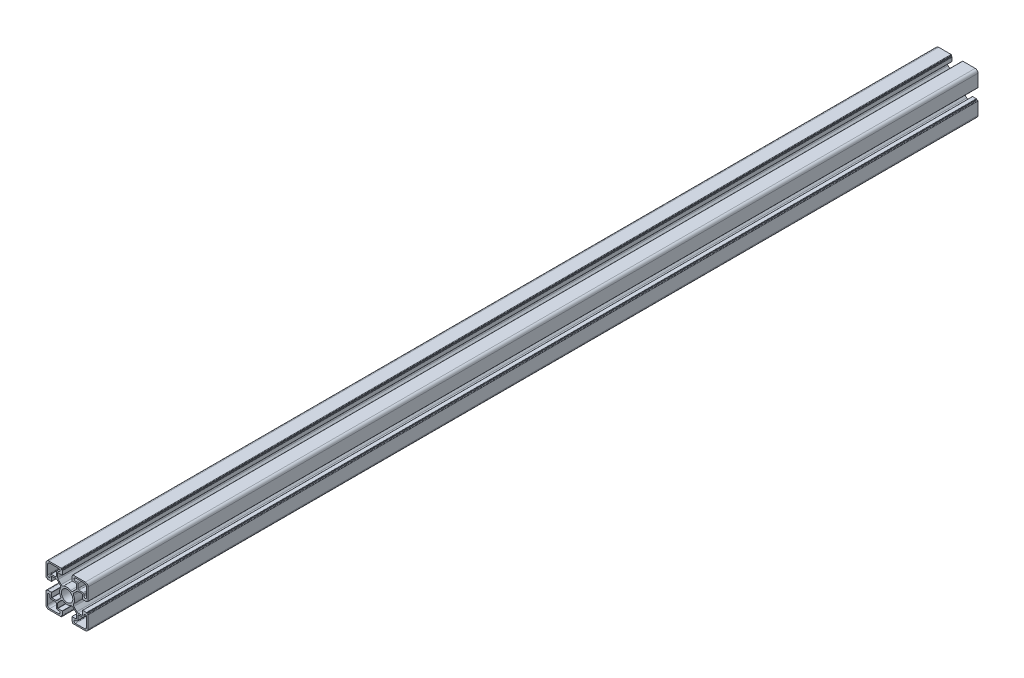
SolidWorks part; units mm, degrees
ref_plane "Front Plane" through (0, 0, 0) normal (0, 0, 1) x (1, 0, 0)
ref_plane "Top Plane" through (0, 0, 0) normal (0, 1, 0) x (1, 0, 0)
ref_plane "Right Plane" through (0, 0, 0) normal (1, 0, 0) x (0, 0, -1)
sketch "Sketch1" plane through (0, 0, 0) normal (0, 0, 1) x (1, 0, 0)
  line L3 (-22.5, 19.5) -> (-22.5, 6.3)
  line L4 (-20.7, 5) -> (-16.7, 5)
  line L5 (-16.5, 5.2) -> (-16.5, 9.8)
  line L6 (-16.3, 10) -> (-11.8642, 10)
  line L7 (-10.4924, 9.4318) -> (-7.2967, 6.236)
  line L8 (-21, 18.5) -> (-21, 9)
  line L9 (-16.5, 5) -> (-16.5, 10) construction
  line L10 (-18, 9) -> (-18, 10.5)
  line L11 (-17, 11.5) -> (-12.5, 11.5)
  line L12 (-22, 5.8) -> (-21.3, 5.8)
  line L13 (-21, 5.5) -> (-21, 5.3)
  line L14 (-21, 22.5) -> (-21, 6.5) construction
  line L15 (-18, 11.5) -> (-10.4393, 11.5) construction
  line L16 (-10.4393, 11.5) -> (-5.1016, 6.1623) construction
  line L17 (-18, 6.5) -> (-18, 11.5) construction
  line L18 (-22.5, 22.5) -> (-22.5, 5) construction
  line L19 (-22.5, 5) -> (-16.5, 5) construction
  line L20 (-21, 6.5) -> (-18, 6.5) construction
  line L21 (-16.5, 10) -> (-11.0607, 10) construction
  line L22 (-11.0607, 10) -> (-6.1623, 5.1016) construction
  line L23 (-5.5, 21) -> (-5.3, 21)
  line L24 (-5.8, 22) -> (-5.8, 21.3)
  line L25 (-11.5, 17) -> (-11.5, 12.5)
  line L26 (-9, 18) -> (-10.5, 18)
  line L27 (-18.5, 21) -> (-9, 21)
  line L28 (-9.4318, 10.4924) -> (-6.236, 7.2967)
  line L29 (-10, 16.3) -> (-10, 11.8642)
  line L30 (-5.2, 16.5) -> (-9.8, 16.5)
  line L31 (-5, 20.7) -> (-5, 16.7)
  line L32 (-19.5, 22.5) -> (-6.3, 22.5)
  line L33 (19.5, 22.5) -> (6.3, 22.5)
  line L34 (5, 20.7) -> (5, 16.7)
  line L35 (5.2, 16.5) -> (9.8, 16.5)
  line L36 (10, 16.3) -> (10, 11.8642)
  line L37 (9.4318, 10.4924) -> (6.236, 7.2967)
  line L38 (18.5, 21) -> (9, 21)
  line L39 (9, 18) -> (10.5, 18)
  line L40 (11.5, 17) -> (11.5, 12.5)
  line L41 (5.8, 22) -> (5.8, 21.3)
  line L42 (5.5, 21) -> (5.3, 21)
  line L43 (21, 5.5) -> (21, 5.3)
  line L44 (22, 5.8) -> (21.3, 5.8)
  line L45 (17, 11.5) -> (12.5, 11.5)
  line L46 (18, 9) -> (18, 10.5)
  line L47 (21, 18.5) -> (21, 9)
  line L48 (10.4924, 9.4318) -> (7.2967, 6.236)
  line L49 (16.3, 10) -> (11.8642, 10)
  line L50 (16.5, 5.2) -> (16.5, 9.8)
  line L51 (20.7, 5) -> (16.7, 5)
  line L52 (22.5, 19.5) -> (22.5, 6.3)
  line L53 (22.5, -19.5) -> (22.5, -6.3)
  line L54 (20.7, -5) -> (16.7, -5)
  line L55 (16.5, -5.2) -> (16.5, -9.8)
  line L56 (16.3, -10) -> (11.8642, -10)
  line L57 (10.4924, -9.4318) -> (7.2967, -6.236)
  line L58 (21, -18.5) -> (21, -9)
  line L59 (18, -9) -> (18, -10.5)
  line L60 (17, -11.5) -> (12.5, -11.5)
  line L61 (22, -5.8) -> (21.3, -5.8)
  line L62 (21, -5.5) -> (21, -5.3)
  line L63 (5.5, -21) -> (5.3, -21)
  line L64 (5.8, -22) -> (5.8, -21.3)
  line L65 (11.5, -17) -> (11.5, -12.5)
  line L66 (9, -18) -> (10.5, -18)
  line L67 (18.5, -21) -> (9, -21)
  line L68 (9.4318, -10.4924) -> (6.236, -7.2967)
  line L69 (10, -16.3) -> (10, -11.8642)
  line L70 (5.2, -16.5) -> (9.8, -16.5)
  line L71 (5, -20.7) -> (5, -16.7)
  line L72 (19.5, -22.5) -> (6.3, -22.5)
  line L73 (-19.5, -22.5) -> (-6.3, -22.5)
  line L74 (-5, -20.7) -> (-5, -16.7)
  line L75 (-5.2, -16.5) -> (-9.8, -16.5)
  line L76 (-10, -16.3) -> (-10, -11.8642)
  line L77 (-9.4318, -10.4924) -> (-6.236, -7.2967)
  line L78 (-18.5, -21) -> (-9, -21)
  line L79 (-9, -18) -> (-10.5, -18)
  line L80 (-11.5, -17) -> (-11.5, -12.5)
  line L81 (-5.8, -22) -> (-5.8, -21.3)
  line L82 (-5.5, -21) -> (-5.3, -21)
  line L83 (-21, -5.5) -> (-21, -5.3)
  line L84 (-22, -5.8) -> (-21.3, -5.8)
  line L85 (-17, -11.5) -> (-12.5, -11.5)
  line L86 (-18, -9) -> (-18, -10.5)
  line L87 (-21, -18.5) -> (-21, -9)
  line L88 (-10.4924, -9.4318) -> (-7.2967, -6.236)
  line L89 (-16.3, -10) -> (-11.8642, -10)
  line L90 (-16.5, -5.2) -> (-16.5, -9.8)
  line L91 (-20.7, -5) -> (-16.7, -5)
  line L92 (-22.5, -19.5) -> (-22.5, -6.3)
  arc A0 (0, 6.1) -> (-6.1, 0) centre (0, 0) ccw
  arc A1 (-6.9766, 3.9149) -> (-8, 0) centre (0, 0) ccw
  arc A2 (-21, 9) -> (-18, 9) centre (-19.5, 9) ccw
  arc A3 (-22, 5.8) -> (-22.5, 6.3) centre (-22, 6.3) cw
  arc A4 (-21, 5.3) -> (-20.7, 5) centre (-20.7, 5.3) ccw
  arc A5 (-21.3, 5.8) -> (-21, 5.5) centre (-21.3, 5.5) cw
  arc A6 (-16.7, 5) -> (-16.5, 5.2) centre (-16.7, 5.2) ccw
  arc A7 (-16.5, 9.8) -> (-16.3, 10) centre (-16.3, 9.8) cw
  arc A8 (-7.2967, 6.236) -> (-6.9766, 3.9149) centre (-8.6685, 4.8643) cw
  arc A9 (-11.8642, 10) -> (-10.4924, 9.4318) centre (-11.8642, 8.06) cw
  arc A10 (-18, 10.5) -> (-17, 11.5) centre (-17, 10.5) cw
  arc A11 (-10.5, 18) -> (-11.5, 17) centre (-10.5, 17) ccw
  arc A12 (-10, 11.8642) -> (-9.4318, 10.4924) centre (-8.06, 11.8642) ccw
  arc A13 (-6.236, 7.2967) -> (-3.9149, 6.9766) centre (-4.8643, 8.6685) ccw
  arc A14 (-9.8, 16.5) -> (-10, 16.3) centre (-9.8, 16.3) ccw
  arc A15 (-5, 16.7) -> (-5.2, 16.5) centre (-5.2, 16.7) cw
  arc A16 (-5.8, 21.3) -> (-5.5, 21) centre (-5.5, 21.3) ccw
  arc A17 (-5.3, 21) -> (-5, 20.7) centre (-5.3, 20.7) cw
  arc A18 (-5.8, 22) -> (-6.3, 22.5) centre (-6.3, 22) ccw
  arc A19 (-9, 21) -> (-9, 18) centre (-9, 19.5) cw
  arc A20 (-3.9149, 6.9766) -> (0, 8) centre (0, 0) cw
  arc A21 (-21, 18.5) -> (-18.5, 21) centre (-18.5, 18.5) cw
  arc A22 (-22.5, 19.5) -> (-19.5, 22.5) centre (-19.5, 19.5) cw
  arc A23 (-12.5, 11.5) -> (-11.5, 12.5) centre (-12.5, 12.5) ccw
  arc A24 (6.1, 0) -> (0, 6.1) centre (0, 0) ccw
  arc A25 (3.9149, 6.9766) -> (0, 8) centre (0, 0) ccw
  arc A26 (9, 21) -> (9, 18) centre (9, 19.5) ccw
  arc A27 (5.8, 22) -> (6.3, 22.5) centre (6.3, 22) cw
  arc A28 (5.3, 21) -> (5, 20.7) centre (5.3, 20.7) ccw
  arc A29 (5.8, 21.3) -> (5.5, 21) centre (5.5, 21.3) cw
  arc A30 (5, 16.7) -> (5.2, 16.5) centre (5.2, 16.7) ccw
  arc A31 (9.8, 16.5) -> (10, 16.3) centre (9.8, 16.3) cw
  arc A32 (6.236, 7.2967) -> (3.9149, 6.9766) centre (4.8643, 8.6685) cw
  arc A33 (10, 11.8642) -> (9.4318, 10.4924) centre (8.06, 11.8642) cw
  arc A34 (10.5, 18) -> (11.5, 17) centre (10.5, 17) cw
  arc A35 (18, 10.5) -> (17, 11.5) centre (17, 10.5) ccw
  arc A36 (11.8642, 10) -> (10.4924, 9.4318) centre (11.8642, 8.06) ccw
  arc A37 (7.2967, 6.236) -> (6.9766, 3.9149) centre (8.6685, 4.8643) ccw
  arc A38 (16.5, 9.8) -> (16.3, 10) centre (16.3, 9.8) ccw
  arc A39 (16.7, 5) -> (16.5, 5.2) centre (16.7, 5.2) cw
  arc A40 (21.3, 5.8) -> (21, 5.5) centre (21.3, 5.5) ccw
  arc A41 (21, 5.3) -> (20.7, 5) centre (20.7, 5.3) cw
  arc A42 (22, 5.8) -> (22.5, 6.3) centre (22, 6.3) ccw
  arc A43 (21, 9) -> (18, 9) centre (19.5, 9) cw
  arc A44 (6.9766, 3.9149) -> (8, 0) centre (0, 0) cw
  arc A45 (18.5, 21) -> (21, 18.5) centre (18.5, 18.5) cw
  arc A46 (19.5, 22.5) -> (22.5, 19.5) centre (19.5, 19.5) cw
  arc A47 (11.5, 12.5) -> (12.5, 11.5) centre (12.5, 12.5) ccw
  arc A48 (0, -6.1) -> (6.1, 0) centre (0, 0) ccw
  arc A49 (6.9766, -3.9149) -> (8, 0) centre (0, 0) ccw
  arc A50 (21, -9) -> (18, -9) centre (19.5, -9) ccw
  arc A51 (22, -5.8) -> (22.5, -6.3) centre (22, -6.3) cw
  arc A52 (21, -5.3) -> (20.7, -5) centre (20.7, -5.3) ccw
  arc A53 (21.3, -5.8) -> (21, -5.5) centre (21.3, -5.5) cw
  arc A54 (16.7, -5) -> (16.5, -5.2) centre (16.7, -5.2) ccw
  arc A55 (16.5, -9.8) -> (16.3, -10) centre (16.3, -9.8) cw
  arc A56 (7.2967, -6.236) -> (6.9766, -3.9149) centre (8.6685, -4.8643) cw
  arc A57 (11.8642, -10) -> (10.4924, -9.4318) centre (11.8642, -8.06) cw
  arc A58 (18, -10.5) -> (17, -11.5) centre (17, -10.5) cw
  arc A59 (10.5, -18) -> (11.5, -17) centre (10.5, -17) ccw
  arc A60 (10, -11.8642) -> (9.4318, -10.4924) centre (8.06, -11.8642) ccw
  arc A61 (6.236, -7.2967) -> (3.9149, -6.9766) centre (4.8643, -8.6685) ccw
  arc A62 (9.8, -16.5) -> (10, -16.3) centre (9.8, -16.3) ccw
  arc A63 (5, -16.7) -> (5.2, -16.5) centre (5.2, -16.7) cw
  arc A64 (5.8, -21.3) -> (5.5, -21) centre (5.5, -21.3) ccw
  arc A65 (5.3, -21) -> (5, -20.7) centre (5.3, -20.7) cw
  arc A66 (5.8, -22) -> (6.3, -22.5) centre (6.3, -22) ccw
  arc A67 (9, -21) -> (9, -18) centre (9, -19.5) cw
  arc A68 (3.9149, -6.9766) -> (0, -8) centre (0, 0) cw
  arc A69 (21, -18.5) -> (18.5, -21) centre (18.5, -18.5) cw
  arc A70 (22.5, -19.5) -> (19.5, -22.5) centre (19.5, -19.5) cw
  arc A71 (12.5, -11.5) -> (11.5, -12.5) centre (12.5, -12.5) ccw
  arc A72 (-6.1, 0) -> (0, -6.1) centre (0, 0) ccw
  arc A73 (-3.9149, -6.9766) -> (0, -8) centre (0, 0) ccw
  arc A74 (-9, -21) -> (-9, -18) centre (-9, -19.5) ccw
  arc A75 (-5.8, -22) -> (-6.3, -22.5) centre (-6.3, -22) cw
  arc A76 (-5.3, -21) -> (-5, -20.7) centre (-5.3, -20.7) ccw
  arc A77 (-5.8, -21.3) -> (-5.5, -21) centre (-5.5, -21.3) cw
  arc A78 (-5, -16.7) -> (-5.2, -16.5) centre (-5.2, -16.7) ccw
  arc A79 (-9.8, -16.5) -> (-10, -16.3) centre (-9.8, -16.3) cw
  arc A80 (-6.236, -7.2967) -> (-3.9149, -6.9766) centre (-4.8643, -8.6685) cw
  arc A81 (-10, -11.8642) -> (-9.4318, -10.4924) centre (-8.06, -11.8642) cw
  arc A82 (-10.5, -18) -> (-11.5, -17) centre (-10.5, -17) cw
  arc A83 (-18, -10.5) -> (-17, -11.5) centre (-17, -10.5) ccw
  arc A84 (-11.8642, -10) -> (-10.4924, -9.4318) centre (-11.8642, -8.06) ccw
  arc A85 (-7.2967, -6.236) -> (-6.9766, -3.9149) centre (-8.6685, -4.8643) ccw
  arc A86 (-16.5, -9.8) -> (-16.3, -10) centre (-16.3, -9.8) ccw
  arc A87 (-16.7, -5) -> (-16.5, -5.2) centre (-16.7, -5.2) cw
  arc A88 (-21.3, -5.8) -> (-21, -5.5) centre (-21.3, -5.5) ccw
  arc A89 (-21, -5.3) -> (-20.7, -5) centre (-20.7, -5.3) cw
  arc A90 (-22, -5.8) -> (-22.5, -6.3) centre (-22, -6.3) ccw
  arc A91 (-21, -9) -> (-18, -9) centre (-19.5, -9) cw
  arc A92 (-6.9766, -3.9149) -> (-8, 0) centre (0, 0) cw
  arc A93 (-18.5, -21) -> (-21, -18.5) centre (-18.5, -18.5) cw
  arc A94 (-19.5, -22.5) -> (-22.5, -19.5) centre (-19.5, -19.5) cw
  arc A95 (-11.5, -12.5) -> (-12.5, -11.5) centre (-12.5, -12.5) ccw
  point P24 (-5.8, 21)
  point P32 (-22.5, 5.8)
  point P35 (-21, 5)
  point P38 (-21, 5.8)
  point P83 (-5, 21)
  point P84 (-5.8, 22.5)
  point P87 (-21, 21)
  point P93 (-11.5, 11.5)
  point P102 (21, 5.8)
  point P158 (21, 5)
  point P159 (22.5, 5.8)
  point P172 (5.8, -21)
  point P228 (5, -21)
  point P229 (5.8, -22.5)
  point P242 (-21, -5.8)
  point P298 (-21, -5)
  point P299 (-22.5, -5.8)
  dimension "D11" = 0.5
  dimension "D12" = 0.3
  dimension "D13" = 0.2
  dimension "D14" = 0.2
  dimension "D6" = 1.94
  dimension "D15" = 1
  dimension "D16" = 2.5
  dimension "D4" = 3
  dimension "D17" = 1
  dimension "D5" = 0.8
  dimension "D7" = 1.5
  dimension "D9" = 1.5
  dimension "D10" = 4
  dimension "D18" = 4
extrude "Boss-Extrude1" add sketch "Sketch1" along normal blind 950
scale "Scale1" scale about centroid uniform scaling yes scale factor 0.564444
